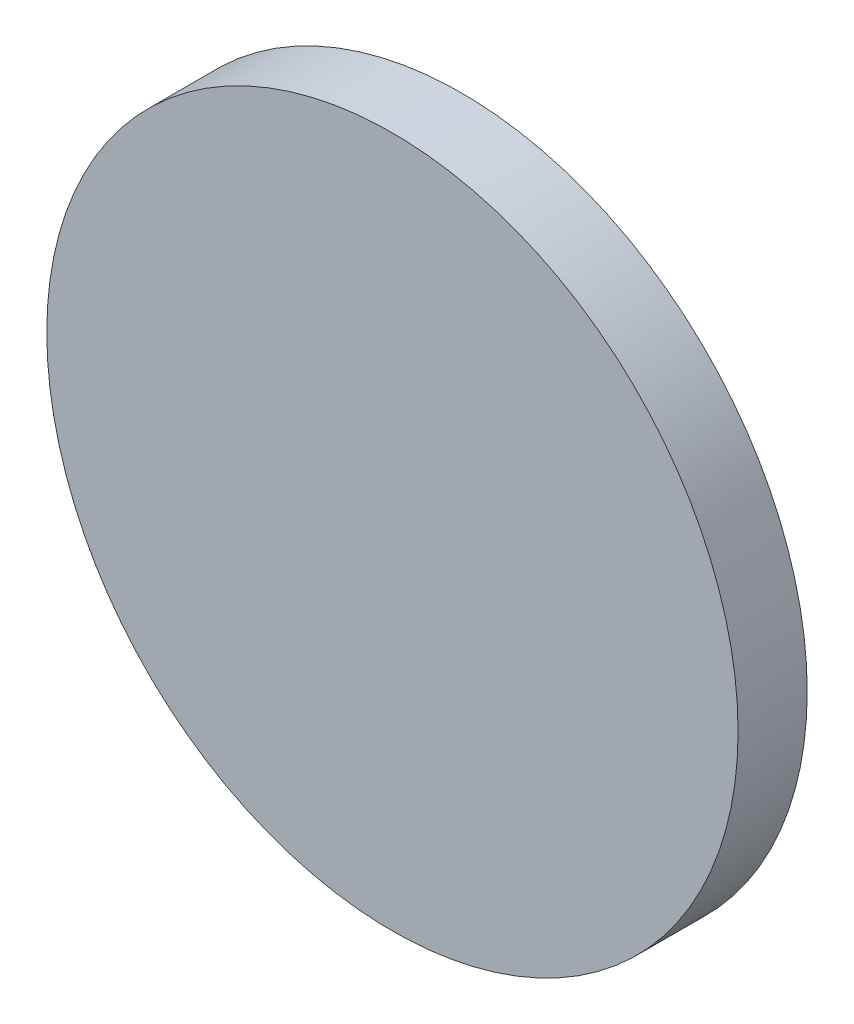
SolidWorks part; units mm, degrees
ref_plane "Спереди" through (0, 0, 0) normal (0, 0, 1) x (1, 0, 0)
ref_plane "Сверху" through (0, 0, 0) normal (0, 1, 0) x (1, 0, 0)
ref_plane "Справа" through (0, 0, 0) normal (1, 0, 0) x (0, 0, -1)
sketch "Эскиз1" plane through (0, 0, 0) normal (0, 0, 1) x (1, 0, 0)
  circle A0 centre (0, 0) radius 50
extrude "Бобышка-Вытянуть1" add sketch "Эскиз1" along normal blind 10
sketch "съемы" plane through (0, 0, 10) normal (0, 0, 1) x (1, 0, 0)
  line L0 (0, 27.8663) -> (0, -27.0911) construction
  line L1 (1, 27.8663) -> (1, -27.0911)
  line L2 (-1, 27.8663) -> (-1, -27.0911)
  arc A0 (1, 27.8663) -> (-1, 27.8663) centre (0, 27.8663) ccw
  arc A1 (-1, -27.0911) -> (1, -27.0911) centre (0, -27.0911) ccw
  point P3 (0, 0.3876)
  point P8 (0, -19.3385)
  point P9 (0, 24.9376)
  point P10 (0, -23.2148)
  point P11 (0, -27.0911)
  point P12 (0, 27.8663)
sketch "ложемент" plane through (0, 0, 10) normal (0, 0, 1) x (1, 0, 0)
  spline S0 degree 3 poles (0, 18.1) (-9.9963, 18.1) (-18.1, 9.9964) (-18.1, 0) knots 0 0 0 0 0.2 0.2 0.2 0.2
  spline S1 degree 3 poles (-18.1, 0) (-18.1, -9.9963) (-9.9964, -18.1) (0, -18.1) knots 0.2 0.2 0.2 0.2 0.4 0.4 0.4 0.4
  spline S2 degree 3 poles (0, -18.1) (9.9963, -18.1) (18.1, -9.9964) (18.1, -0.0001) knots 0.4 0.4 0.4 0.4 0.6 0.6 0.6 0.6
  spline S3 degree 3 poles (18.1, -0.0001) (18.1, 9.9963) (9.9964, 18.0999) (0.0001, 18.1) knots 0.6 0.6 0.6 0.6 1 1 1 1
sketch "остров" plane through (0, 0, 10) normal (0, 0, 1) x (1, 0, 0)
  spline S5 degree 3 poles (-9.5, 5.5) (-12.5376, 5.5) (-15, 3.0376) (-15, 0) knots 0 0 0 0 0.2 0.2 0.2 0.2
  spline S6 degree 3 poles (-15, 0) (-15, -3.0376) (-12.5376, -5.5) (-9.5, -5.5) knots 0.2 0.2 0.2 0.2 0.4 0.4 0.4 0.4
  spline S7 degree 3 poles (-9.5, -5.5) (-6.4625, -5.5) (-4, -3.0376) (-4, 0) knots 0.4 0.4 0.4 0.4 0.6 0.6 0.6 0.6
  spline S8 degree 3 poles (-4, 0) (-4, 3.0375) (-6.4624, 5.5) (-9.5, 5.5) knots 0.6 0.6 0.6 0.6 1 1 1 1
sketch "pazik" plane through (0, 0, 10) normal (0, 0, 1) x (1, 0, 0)
  line L0 (-16.3651, 0) -> (-28.6865, 0) construction
  line L1 (-16.3651, -1) -> (-28.6865, -1)
  line L2 (-16.3651, 1) -> (-28.6865, 1)
  arc A0 (-16.3651, -1) -> (-16.3651, 1) centre (-16.3651, 0) ccw
  arc A1 (-28.6865, 1) -> (-28.6865, -1) centre (-28.6865, 0) ccw
  point P3 (-22.5258, 0)
  point P8 (0, 0)
sketch "сверление" plane through (0, 0, 10) normal (0, 0, 1) x (1, 0, 0)
  line L0 (0, 27.8663) -> (0, -27.0911) construction
  circle A0 centre (0, 5.081) radius 0.5
  circle A1 centre (0, 4.581) radius 0.5
  circle A2 centre (0, 4.081) radius 0.5
  circle A3 centre (0, 3.581) radius 0.5
  circle A4 centre (0, 3.081) radius 0.5
  circle A5 centre (0, 2.581) radius 0.5
  circle A6 centre (0, 2.081) radius 0.5
  circle A7 centre (0, 1.581) radius 0.5
  circle A8 centre (0, 1.081) radius 0.5
  circle A9 centre (0, 0.581) radius 0.5
  circle A10 centre (0, 0.081) radius 0.5
  circle A11 centre (0, -0.419) radius 0.5
  circle A12 centre (0, -0.919) radius 0.5
  circle A13 centre (0, -1.419) radius 0.5
  circle A14 centre (0, -1.919) radius 0.5
  circle A15 centre (0, -2.419) radius 0.5
  circle A16 centre (0, -2.919) radius 0.5
  circle A17 centre (0, -3.419) radius 0.5
  circle A18 centre (0, -3.919) radius 0.5
  circle A19 centre (0, -4.419) radius 0.5
  circle A40 centre (0, -4.919) radius 0.5
  circle A41 centre (0, -5.419) radius 0.5
  circle A42 centre (0, -5.919) radius 0.5
  circle A43 centre (0, -6.419) radius 0.5
  circle A44 centre (0, -6.919) radius 0.5
  circle A45 centre (0, -7.419) radius 0.5
  circle A46 centre (0, -7.919) radius 0.5
  circle A47 centre (0, -8.419) radius 0.5
  circle A48 centre (0, -8.919) radius 0.5
  circle A49 centre (0, -9.419) radius 0.5
  circle A50 centre (0, -9.919) radius 0.5
  circle A51 centre (0, -10.419) radius 0.5
  circle A52 centre (0, -10.919) radius 0.5
  circle A53 centre (0, -11.419) radius 0.5
  circle A54 centre (0, -11.919) radius 0.5
  circle A55 centre (0, -12.419) radius 0.5
  circle A56 centre (0, -12.919) radius 0.5
  circle A57 centre (0, -13.419) radius 0.5
  circle A58 centre (0, -13.919) radius 0.5
  circle A59 centre (0, -14.419) radius 0.5
  dimension "D1" = 40
sketch "планирование" plane through (0, 0, 10) normal (0, 0, 1) x (1, 0, 0)
  line L1 (-32.5, -32.5) -> (32.5, -32.5)
  line L2 (-32.5, -32.5) -> (-32.5, 32.5)
  line L3 (-32.5, 32.5) -> (32.5, 32.5)
  line L4 (32.5, -32.5) -> (32.5, 32.5)
  line L5 (-32.5, -32.5) -> (32.5, 32.5) construction
  line L6 (-32.5, 32.5) -> (32.5, -32.5) construction
  point P0 (0, 0)
sketch "непрерывная шлифовка" plane through (0, 0, 10) normal (0, 0, 1) x (1, 0, 0)
  line L0 (0, -15.9554) -> (0, 15.6045) construction
  line L1 (-0.5, -15.9554) -> (-0.5, 15.6045)
  line L2 (0.5, -15.9554) -> (0.5, 15.6045)
  arc A0 (-0.5, -15.9554) -> (0.5, -15.9554) centre (0, -15.9554) ccw
  arc A1 (0.5, 15.6045) -> (-0.5, 15.6045) centre (0, 15.6045) ccw
  point P3 (0, -0.1755)
